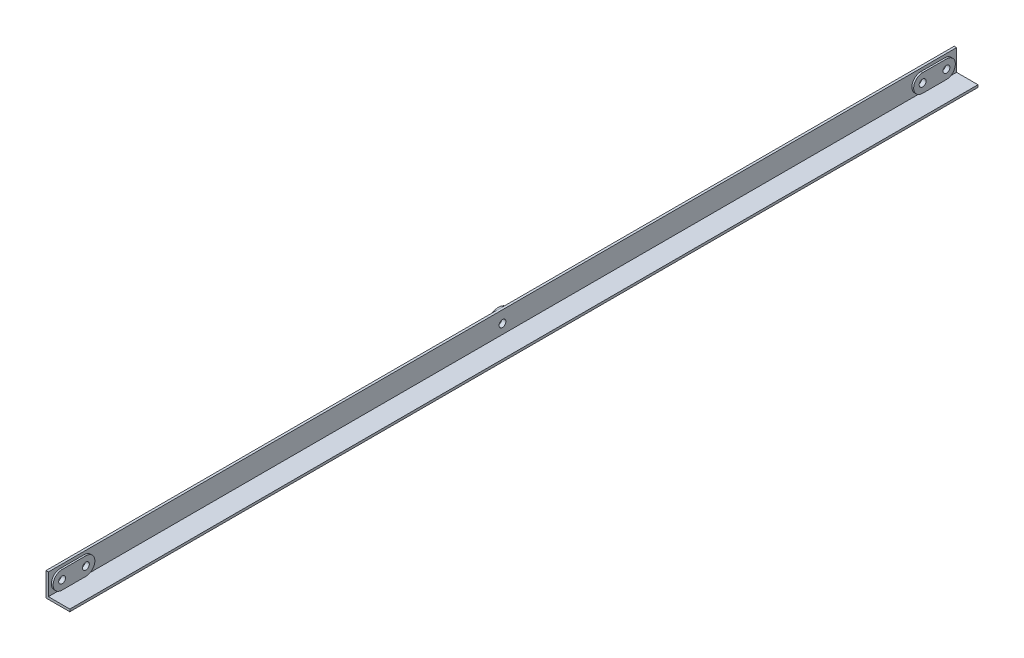
SolidWorks part; units mm, degrees
ref_plane "前视基准面" through (0, 0, 0) normal (0, 0, 1) x (1, 0, 0)
ref_plane "上视基准面" through (0, 0, 0) normal (0, 1, 0) x (1, 0, 0)
ref_plane "右视基准面" through (0, 0, 0) normal (1, 0, 0) x (0, 0, -1)
sketch "草图1" plane through (0, 0, 0) normal (0, 0, 1) x (1, 0, 0)
  line L1 (0, 0) -> (80, 0)
  line L2 (0, 0) -> (0, 80)
  line L3 (0, 80) -> (80, 80)
  line L4 (80, 0) -> (80, 80)
  dimension "D1" = 80
  dimension "D2" = 80
extrude "凸台-拉伸1" add sketch "草图1" along normal blind 3050
sketch "草图2" plane through (0, 0, 3050) normal (0, 0, 1) x (1, 0, 0)
  line L0 (0, 80) -> (0, 0) construction
  line L1 (80, 80) -> (8, 80)
  line L2 (80, 80) -> (80, 8)
  line L3 (80, 8) -> (8, 8)
  line L4 (8, 80) -> (8, 8)
  line L5 (0, 0) -> (80, 0) construction
  dimension "D1" = 8
  dimension "D2" = 8
extrude "切除-拉伸1" cut sketch "草图2" against normal through all
sketch "草图5" plane through (0, 0, 0) normal (-1, 0, 0) x (0, 0, 1)
  line L0 (1525, 80) -> (1525, 0) construction
  line L1 (3050, 80) -> (0, 80) construction
  line L2 (3050, 0) -> (0, 0) construction
  circle A1 centre (1525, 40) radius 40
  dimension "D1" = 80
extrude "凸台-拉伸2" add sketch "草图5" along normal blind 6
sketch "草图6" plane through (-6, 0, 0) normal (-1, 0, 0) x (0, 0, 1)
  circle A0 centre (1525, 40) radius 11.5
  circle A1 centre (1525, 40) radius 40 construction
  dimension "D1" = 23
extrude "切除-拉伸2" cut sketch "草图6" against normal through all
sketch "草图7" plane through (8, 0, 0) normal (1, 0, 0) x (0, 0, -1)
  line L0 (-3050, 80) -> (-3050, 8) construction
  line L2 (0, 80) -> (-3050, 80) construction
  circle A0 centre (-3010, 40) radius 30
  circle A1 centre (-2930, 40) radius 30
  dimension "D1" = 60
  dimension "D4" = 60
  dimension "D2" = 40
  dimension "D3" = 40
  dimension "D5" = 40
  dimension "D6" = 80
extrude "凸台-拉伸3" add sketch "草图7" along normal blind 6
sketch "草图8" plane through (8, 0, 0) normal (1, 0, 0) x (0, 0, -1)
  line L0 (-3050, 80) -> (-3050, 8) construction
  line L1 (-3010, 70) -> (-2930, 70)
  line L2 (-3010, 70) -> (-3010, 10)
  line L3 (-3010, 10) -> (-2930, 10)
  line L4 (-2930, 70) -> (-2930, 10)
  line L5 (0, 80) -> (-3050, 80) construction
  dimension "D1" = 80
  dimension "D2" = 60
  dimension "D3" = 40
  dimension "D4" = 10
extrude "凸台-拉伸4" add sketch "草图8" along normal blind 6
sketch "草图9" plane through (0, 0, 0) normal (-1, 0, 0) x (0, 0, 1)
  line L0 (3050, 80) -> (1525, 80) construction
  line L1 (3050, 80) -> (3050, 0) construction
  circle A0 centre (3010, 40) radius 11.5
  circle A1 centre (2930, 40) radius 11.5
  dimension "D1" = 23
  dimension "D2" = 23
  dimension "D3" = 40
  dimension "D4" = 40
  dimension "D5" = 80
  dimension "D6" = 40
extrude "切除-拉伸3" cut sketch "草图9" against normal through all
ref_plane "基准面1" through (0, 0, 1525) normal (0, 0, 1) x (1, 0, 0)
mirror "镜向1" about plane through (0, 0, 1525) normal (0, 0, 1) of "切除-拉伸3", "凸台-拉伸4", "凸台-拉伸3"
